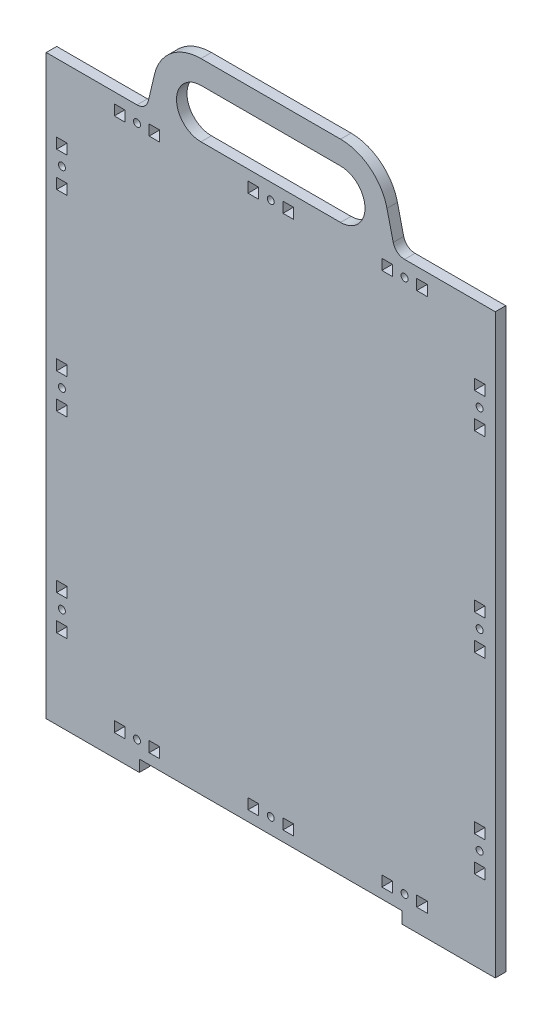
SolidWorks part; units mm, degrees
ref_plane "Front Plane" through (0, 0, 0) normal (0, 0, 1) x (1, 0, 0)
ref_plane "Top Plane" through (0, 0, 0) normal (0, 1, 0) x (1, 0, 0)
ref_plane "Right Plane" through (0, 0, 0) normal (1, 0, 0) x (0, 0, -1)
sketch "Sketch1" plane through (0, 0, 0) normal (0, 0, 1) x (1, 0, 0)
  line L0 (-193, 243) -> (-193, -253)
  line L1 (-175, -225) -> (175, -225) construction
  line L2 (-175, -225) -> (-175, 225) construction
  line L3 (-175, 225) -> (175, 225) construction
  line L4 (175, -225) -> (175, 225) construction
  line L5 (-175, -225) -> (175, 225) construction
  line L6 (-175, 225) -> (175, -225) construction
  line L7 (-193, -253) -> (-113, -253)
  line L8 (-113, -253) -> (-113, -243)
  line L9 (-113, -243) -> (113, -243)
  line L10 (113, -243) -> (113, -253)
  line L11 (113, -253) -> (193, -253)
  line L12 (193, -253) -> (193, 243)
  line L13 (193, 243) -> (115, 243)
  line L14 (105.2676, 250.7019) -> (99.9026, 273.4223)
  line L15 (60, 305) -> (-60, 305)
  line L16 (-99.9026, 273.4223) -> (-105.2676, 250.7019)
  line L17 (-115, 243) -> (-193, 243)
  line L18 (0, 0) -> (0, -193.9538) construction
  line L19 (-60, 264) -> (60, 264) construction
  line L20 (-60, 285) -> (60, 285)
  line L21 (-60, 243) -> (60, 243)
  line L22 (0, 0) -> (147.3741, 0) construction
  arc A0 (-60, 285) -> (-60, 243) centre (-60, 264) ccw
  arc A1 (60, 243) -> (60, 285) centre (60, 264) ccw
  arc A2 (60, 305) -> (99.9026, 273.4223) centre (60, 264) cw
  arc A3 (-60, 305) -> (-99.9026, 273.4223) centre (-60, 264) ccw
  arc A4 (-105.2676, 250.7019) -> (-115, 243) centre (-115, 253) cw
  arc A5 (115, 243) -> (105.2676, 250.7019) centre (115, 253) cw
  point P0 (0, 0)
  point P22 (0, 264)
  line B0 (115, 234.9951) -> (115, 224.5131) construction
  line B1 (134.525, 234.05) -> (125.475, 234.05)
  line B2 (95.475, 225) -> (104.525, 225)
  line B3 (95.475, 225) -> (95.475, 234.05)
  line B4 (95.475, 234.05) -> (104.525, 234.05)
  line B5 (104.525, 225) -> (104.525, 234.05)
  line B6 (125.475, 225) -> (125.475, 234.05)
  line B7 (134.525, 225) -> (125.475, 225)
  line B8 (134.525, 225) -> (134.525, 234.05)
  circle B9 centre (115, 229.525) radius 3
  line B10 (174.0549, 0) -> (184.5369, 0) construction
  line B11 (175, 19.525) -> (175, 10.475)
  line B12 (184.05, -19.525) -> (184.05, -10.475)
  line B13 (184.05, -19.525) -> (175, -19.525)
  line B14 (175, -19.525) -> (175, -10.475)
  line B15 (184.05, -10.475) -> (175, -10.475)
  line B16 (184.05, 10.475) -> (175, 10.475)
  line B17 (184.05, 19.525) -> (184.05, 10.475)
  line B18 (184.05, 19.525) -> (175, 19.525)
  circle B19 centre (179.525, 0) radius 3
  line B20 (174.0549, 165) -> (184.5369, 165) construction
  line B21 (175, 184.525) -> (175, 175.475)
  line B22 (184.05, 145.475) -> (184.05, 154.525)
  line B23 (184.05, 145.475) -> (175, 145.475)
  line B24 (175, 145.475) -> (175, 154.525)
  line B25 (184.05, 154.525) -> (175, 154.525)
  line B26 (184.05, 175.475) -> (175, 175.475)
  line B27 (184.05, 184.525) -> (184.05, 175.475)
  line B28 (184.05, 184.525) -> (175, 184.525)
  circle B29 centre (179.525, 165) radius 3
  line B30 (0, 234.9951) -> (0, 224.5131) construction
  line B31 (19.525, 234.05) -> (10.475, 234.05)
  line B32 (-19.525, 225) -> (-10.475, 225)
  line B33 (-19.525, 225) -> (-19.525, 234.05)
  line B34 (-19.525, 234.05) -> (-10.475, 234.05)
  line B35 (-10.475, 225) -> (-10.475, 234.05)
  line B36 (10.475, 225) -> (10.475, 234.05)
  line B37 (19.525, 225) -> (10.475, 225)
  line B38 (19.525, 225) -> (19.525, 234.05)
  circle B39 centre (0, 229.525) radius 3
  line B40 (-175, 19.525) -> (-175, 10.475)
  line B41 (-184.05, -19.525) -> (-184.05, -10.475)
  line B42 (-184.05, -19.525) -> (-175, -19.525)
  line B43 (-175, -19.525) -> (-175, -10.475)
  line B44 (-184.05, -10.475) -> (-175, -10.475)
  line B45 (-184.05, 10.475) -> (-175, 10.475)
  line B46 (-184.05, 19.525) -> (-184.05, 10.475)
  line B47 (-184.05, 19.525) -> (-175, 19.525)
  circle B48 centre (-179.525, 0) radius 3
  line B49 (-134.525, 234.05) -> (-125.475, 234.05)
  line B50 (-95.475, 225) -> (-104.525, 225)
  line B51 (-95.475, 225) -> (-95.475, 234.05)
  line B52 (-95.475, 234.05) -> (-104.525, 234.05)
  line B53 (-104.525, 225) -> (-104.525, 234.05)
  line B54 (-125.475, 225) -> (-125.475, 234.05)
  line B55 (-134.525, 225) -> (-125.475, 225)
  line B56 (-134.525, 225) -> (-134.525, 234.05)
  circle B57 centre (-115, 229.525) radius 3
  line B58 (-175, 184.525) -> (-175, 175.475)
  line B59 (-184.05, 145.475) -> (-184.05, 154.525)
  line B60 (-184.05, 145.475) -> (-175, 145.475)
  line B61 (-175, 145.475) -> (-175, 154.525)
  line B62 (-184.05, 154.525) -> (-175, 154.525)
  line B63 (-184.05, 175.475) -> (-175, 175.475)
  line B64 (-184.05, 184.525) -> (-184.05, 175.475)
  line B65 (-184.05, 184.525) -> (-175, 184.525)
  circle B66 centre (-179.525, 165) radius 3
  line B67 (134.525, -234.05) -> (125.475, -234.05)
  line B68 (95.475, -225) -> (104.525, -225)
  line B69 (95.475, -225) -> (95.475, -234.05)
  line B70 (95.475, -234.05) -> (104.525, -234.05)
  line B71 (104.525, -225) -> (104.525, -234.05)
  line B72 (125.475, -225) -> (125.475, -234.05)
  line B73 (134.525, -225) -> (125.475, -225)
  line B74 (134.525, -225) -> (134.525, -234.05)
  circle B75 centre (115, -229.525) radius 3
  line B76 (-134.525, -234.05) -> (-125.475, -234.05)
  line B77 (-95.475, -225) -> (-104.525, -225)
  line B78 (-95.475, -225) -> (-95.475, -234.05)
  line B79 (-95.475, -234.05) -> (-104.525, -234.05)
  line B80 (-104.525, -225) -> (-104.525, -234.05)
  line B81 (-125.475, -225) -> (-125.475, -234.05)
  line B82 (-134.525, -225) -> (-125.475, -225)
  line B83 (-134.525, -225) -> (-134.525, -234.05)
  circle B84 centre (-115, -229.525) radius 3
  line B85 (-175, -184.525) -> (-175, -175.475)
  line B86 (-184.05, -145.475) -> (-184.05, -154.525)
  line B87 (-184.05, -145.475) -> (-175, -145.475)
  line B88 (-175, -145.475) -> (-175, -154.525)
  line B89 (-184.05, -154.525) -> (-175, -154.525)
  line B90 (-184.05, -175.475) -> (-175, -175.475)
  line B91 (-184.05, -184.525) -> (-184.05, -175.475)
  line B92 (-184.05, -184.525) -> (-175, -184.525)
  circle B93 centre (-179.525, -165) radius 3
  line B94 (175, -184.525) -> (175, -175.475)
  line B95 (184.05, -145.475) -> (184.05, -154.525)
  line B96 (184.05, -145.475) -> (175, -145.475)
  line B97 (175, -145.475) -> (175, -154.525)
  line B98 (184.05, -154.525) -> (175, -154.525)
  line B99 (184.05, -175.475) -> (175, -175.475)
  line B100 (184.05, -184.525) -> (184.05, -175.475)
  line B101 (184.05, -184.525) -> (175, -184.525)
  circle B102 centre (179.525, -165) radius 3
  line B103 (19.525, -234.05) -> (10.475, -234.05)
  line B104 (-19.525, -225) -> (-10.475, -225)
  line B105 (-19.525, -225) -> (-19.525, -234.05)
  line B106 (-19.525, -234.05) -> (-10.475, -234.05)
  line B107 (-10.475, -225) -> (-10.475, -234.05)
  line B108 (10.475, -225) -> (10.475, -234.05)
  line B109 (19.525, -225) -> (10.475, -225)
  line B110 (19.525, -225) -> (19.525, -234.05)
  circle B111 centre (0, -229.525) radius 3
  dimension "D12" = 10
  dimension "D13" = 41
  dimension "D14" = 41
  dimension "D1" = 350
  dimension "D2" = 450
  dimension "D3" = 18
  dimension "D4" = 18
  dimension "D5" = 18
  dimension "D6" = 10
  dimension "D7" = 80
  dimension "D8" = 18
  dimension "D9" = 42
  dimension "D10" = 20
  dimension "D11" = 120
  dimension "D15" = 230
  dimension "D16" = 60
  dimension "D17" = 60
sketch_block_instance "Insert_9mm_M6_bois-11"
sketch_block "Insert_9mm_M6_bois" parameters "D4"=6, "D1"=9.05, "D2"=9.05, "D3"=15
sketch_block_instance "Insert_9mm_M6_bois-14"
sketch_block_instance "Insert_9mm_M6_bois-16"
sketch_block_instance "Insert_9mm_M6_bois-21"
sketch_block_instance "Insert_9mm_M6_bois-22"
sketch_block_instance "Insert_9mm_M6_bois-23"
sketch_block_instance "Insert_9mm_M6_bois-24"
sketch_block_instance "Insert_9mm_M6_bois-25"
sketch_block_instance "Insert_9mm_M6_bois-26"
sketch_block_instance "Insert_9mm_M6_bois-27"
sketch_block_instance "Insert_9mm_M6_bois-28"
sketch_block_instance "Insert_9mm_M6_bois-29"
extrude "Boss-Extrude1" add sketch "Sketch1" along normal blind 9
